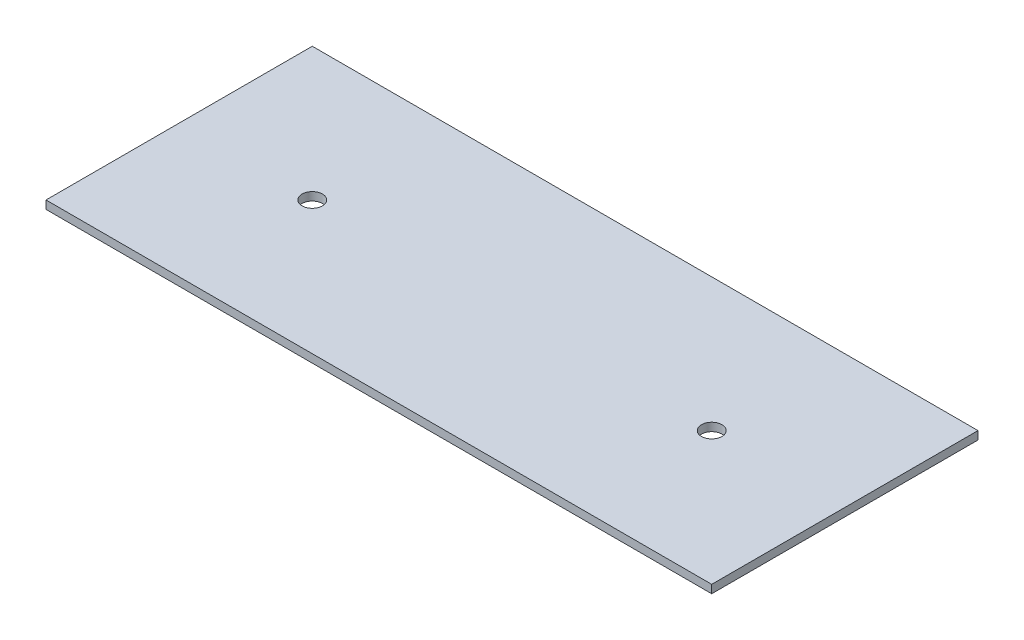
SolidWorks part; units mm, degrees
material "6061 Alloy"
ref_plane "Front Plane" through (0, 0, 0) normal (0, 0, 1) x (1, 0, 0)
ref_plane "Top Plane" through (0, 0, 0) normal (0, 1, 0) x (1, 0, 0)
ref_plane "Right Plane" through (0, 0, 0) normal (1, 0, 0) x (0, 0, -1)
sketch "Sketch1" plane through (0, 0, 0) normal (0, 1, 0) x (1, 0, 0)
  line L0 (-39, 0) -> (39, 0) construction
  line L1 (39, 0) -> (65, 0) construction
  line L2 (-65, -26) -> (65, -26)
  line L3 (-65, -26) -> (-65, 26)
  line L4 (-65, 26) -> (65, 26)
  line L5 (65, -26) -> (65, 26)
  line L6 (-65, -26) -> (65, 26) construction
  line L7 (-65, 26) -> (65, -26) construction
  line L8 (39, 0) -> (39, 26) construction
  circle A0 centre (39, 0) radius 2
  circle A1 centre (-39, 0) radius 2
  point P3 (0, 0)
  dimension "D2" = 4
  dimension "D1" = 78
  dimension "D3" = 26
extrude "Boss-Extrude1" add sketch "Sketch1" along normal blind 1.6
